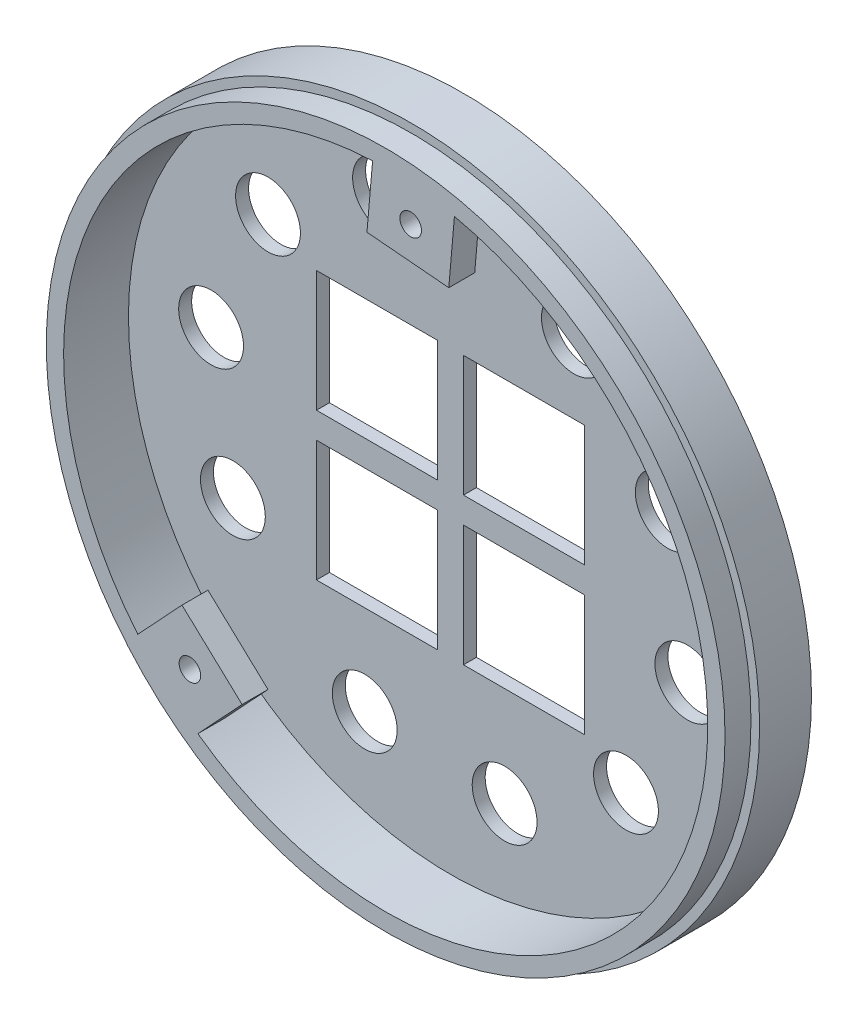
SolidWorks part; units mm, degrees
ref_plane "Front Plane" through (0, 0, 0) normal (1, 0, 0) x (0, 1, 0)
ref_plane "Top Plane" through (0, 0, 0) normal (0, 0, 1) x (0, 1, 0)
ref_plane "Right Plane" through (0, 0, 0) normal (0, 1, 0) x (-1, 0, 0)
sketch "Sketch2" plane through (0, 0, 0) normal (0, 0, 1) x (0, 1, 0)
  line L0 (-39.25, 0) -> (39.25, 0) construction
  line L1 (-23.781, 28.671) -> (30.26, -21.7231)
  line L2 (-30.26, 21.7231) -> (23.781, -28.671)
  line L3 (3.2395, 3.4739) -> (-3.2395, -3.4739) construction
  line L4 (-30.26, -21.7231) -> (23.781, 28.671)
  line L5 (-23.781, -28.671) -> (30.26, 21.7231)
  line L6 (-3.2395, 3.4739) -> (3.2395, -3.4739) construction
  line L7 (-36.3913, 7.952) -> (37.2193, 1.5119)
  line L8 (-37.2193, -1.5119) -> (36.3913, -7.952)
  line L9 (0.414, 4.7319) -> (-0.414, -4.7319) construction
  line L10 (-24.7749, 16.6081) -> (-18.2959, 23.556)
  line L11 (-24.7749, -16.6081) -> (-18.2959, -23.556)
  line L12 (29.7478, 2.1655) -> (28.9199, -7.2983)
  line L13 (-23.781, 28.671) -> (-24.7749, 16.6081) construction
  line L14 (-23.781, -28.671) -> (-24.7749, -16.6081) construction
  line L15 (29.7478, 2.1655) -> (36.3913, -7.952) construction
  circle A0 centre (0, 0) radius 39.25
  circle A1 centre (0, 0) radius 37.25
  circle A2 centre (-24.2779, 22.6396) radius 1.25
  circle A3 centre (-24.2779, -22.6396) radius 1.25
  circle A5 centre (33.0696, -2.8932) radius 1.25
  dimension "D1" = 78.5
  dimension "D12" = 2.5
  dimension "D3" = 9.5
  dimension "D4" = 43
  dimension "D5" = 9.5
  dimension "D6" = 43
  dimension "D7" = 9.5
  dimension "D8" = 5
  dimension "D9" = 7.5
  dimension "D10" = 7.5
  dimension "D11" = 7.5
  dimension "D2" = 2
extrude "Boss-Extrude1" add sketch "Sketch2" along normal blind 3 contours A0 A1 | L1 A1 L2 L10 | L8 A1 L7 L12 A5
sketch "Sketch3" plane through (0, 0, 0) normal (0, 0, 1) x (1, 0, 0)
  circle A0 centre (0, 0) radius 39.25 construction
  circle A1 centre (0, 0) radius 39.25 construction
  circle A2 centre (0, 0) radius 40.25
  circle A3 centre (2.8932, 33.0696) radius 1.25 construction
  circle A5 centre (-22.6396, -24.2779) radius 1.25 construction
  circle A6 centre (2.8932, 33.0696) radius 1.25
  circle A8 centre (-22.6396, -24.2779) radius 1.25
  arc A9 (-1.5119, 37.2193) -> (-28.671, -23.781) centre (0, 0) ccw construction
  arc A10 (-1.5119, 37.2193) -> (-28.671, -23.781) centre (0, 0) ccw construction
  circle A11 centre (0, 0) radius 37.25
  dimension "D1" = 80.5
extrude "Boss-Extrude2" add sketch "Sketch3" against normal blind 6
sketch "Sketch4" plane through (0, 0, -6) normal (0, 0, 1) x (1, 0, 0)
  circle A2 centre (0, 0) radius 40.25 construction
  circle A3 centre (0, 0) radius 40.25
extrude "Boss-Extrude3" add sketch "Sketch4" along normal blind 1.5
sketch "Sketch5" plane through (0, 0, -6) normal (0, 0, -1) x (-1, 0, 0)
  line L1 (-8.5, -8.5) -> (8.5, -8.5) construction
  line L2 (-8.5, -8.5) -> (-8.5, 8.5) construction
  line L3 (-8.5, 8.5) -> (8.5, 8.5) construction
  line L4 (8.5, -8.5) -> (8.5, 8.5) construction
  line L5 (-8.5, -8.5) -> (8.5, 8.5) construction
  line L6 (-8.5, 8.5) -> (8.5, -8.5) construction
  line L7 (-15.5, -1.5) -> (-1.5, -1.5)
  line L8 (-15.5, -1.5) -> (-15.5, -15.5)
  line L9 (-15.5, -15.5) -> (-1.5, -15.5)
  line L10 (-1.5, -1.5) -> (-1.5, -15.5)
  line L11 (-15.5, -1.5) -> (-1.5, -15.5) construction
  line L12 (-15.5, -15.5) -> (-1.5, -1.5) construction
  line L13 (-15.5, 1.5) -> (-1.5, 1.5)
  line L14 (-15.5, 1.5) -> (-15.5, 15.5)
  line L15 (-15.5, 15.5) -> (-1.5, 15.5)
  line L16 (-1.5, 1.5) -> (-1.5, 15.5)
  line L17 (-15.5, 1.5) -> (-1.5, 15.5) construction
  line L18 (-15.5, 15.5) -> (-1.5, 1.5) construction
  line L19 (1.5, 1.5) -> (15.5, 1.5)
  line L20 (1.5, 1.5) -> (1.5, 15.5)
  line L21 (1.5, 15.5) -> (15.5, 15.5)
  line L22 (15.5, 1.5) -> (15.5, 15.5)
  line L23 (1.5, 1.5) -> (15.5, 15.5) construction
  line L24 (1.5, 15.5) -> (15.5, 1.5) construction
  line L25 (1.5, -1.5) -> (15.5, -1.5)
  line L26 (1.5, -1.5) -> (1.5, -15.5)
  line L27 (1.5, -15.5) -> (15.5, -15.5)
  line L28 (15.5, -1.5) -> (15.5, -15.5)
  line L29 (1.5, -1.5) -> (15.5, -15.5) construction
  line L30 (1.5, -15.5) -> (15.5, -1.5) construction
  point P24 (0, 0)
  dimension "D2" = 17
  dimension "D3" = 14
  dimension "D4" = 14
extrude "Cut-Extrude1" cut sketch "Sketch5" against normal up to surface (1.5 mm away) contours L10 L7 L8 L9 | L13 L16 L15 L14 | L19 L22 L21 L20 | L28 L25 L26 L27 up to face at (37.25, 0, -4.5)
sketch "Sketch7" plane through (0, 0, -6) normal (0, 0, -1) x (-1, 0, 0)
  line L0 (-5.6407, -25.115) -> (-8.0671, -26.17) construction
  line L1 (-18.7205, -17.667) -> (-21.322, -17.1848) construction
  line L2 (-25.3992, -4.1783) -> (-27.2864, -2.3238) construction
  line L3 (-23.3934, 10.7391) -> (-23.9209, 13.3319) construction
  line L4 (-13.3887, 21.9846) -> (-12.3762, 24.429) construction
  line L5 (6.994, 24.9791) -> (9.4016, 26.0763) construction
  line L6 (19.5696, 17.0265) -> (22.1841, 16.6202) construction
  line L7 (25.7064, 3.4717) -> (27.6674, 1.6956) construction
  line L8 (23.3851, -11.2253) -> (24.0476, -13.7869) construction
  line L9 (9.3677, -23.9755) -> (7.9461, -26.207) construction
  line L10 (-5.6407, -25.115) -> (-8.0671, -26.17) construction
  line L11 (-18.7205, -17.667) -> (-21.322, -17.1848) construction
  line L12 (-25.3992, -4.1783) -> (-27.2864, -2.3238) construction
  line L13 (-23.3934, 10.7391) -> (-23.9209, 13.3319) construction
  line L14 (-13.3887, 21.9846) -> (-12.3762, 24.429) construction
  line L15 (6.994, 24.9791) -> (9.4016, 26.0763) construction
  line L16 (19.5696, 17.0265) -> (22.1841, 16.6202) construction
  line L17 (25.7064, 3.4717) -> (27.6674, 1.6956) construction
  line L18 (23.3851, -11.2253) -> (24.0476, -13.7869) construction
  line L19 (9.3677, -23.9755) -> (7.9461, -26.207) construction
  arc A0 (-8.0671, -26.17) -> (-5.6407, -25.115) centre (-6.2558, -27.018) ccw construction
  arc A1 (-21.322, -17.1848) -> (-18.7205, -17.667) centre (-20.2946, -18.9008) ccw construction
  arc A2 (-27.2864, -2.3238) -> (-25.3992, -4.1783) centre (-27.3941, -4.3209) ccw construction
  arc A3 (-23.9209, 13.3319) -> (-23.3934, 10.7391) centre (-25.127, 11.7365) ccw construction
  arc A4 (-12.3762, 24.429) -> (-13.3887, 21.9846) centre (-14.2682, 23.7808) ccw construction
  arc A5 (9.4016, 26.0763) -> (6.994, 24.9791) centre (7.5758, 26.8926) ccw construction
  arc A6 (22.1841, 16.6202) -> (19.5696, 17.0265) centre (21.1072, 18.3055) ccw construction
  arc A7 (27.6674, 1.6956) -> (25.7064, 3.4717) centre (27.6938, 3.6954) ccw construction
  arc A8 (24.0476, -13.7869) -> (23.3851, -11.2253) centre (25.1685, -12.1305) ccw construction
  arc A9 (7.9461, -26.207) -> (9.3677, -23.9755) centre (9.922, -25.8972) ccw construction
  arc A10 (-8.0671, -26.17) -> (-5.6407, -25.115) centre (-6.2558, -27.018) ccw construction
  arc A11 (-21.322, -17.1848) -> (-18.7205, -17.667) centre (-20.2946, -18.9008) ccw construction
  arc A12 (-27.2864, -2.3238) -> (-25.3992, -4.1783) centre (-27.3941, -4.3209) ccw construction
  arc A13 (-23.9209, 13.3319) -> (-23.3934, 10.7391) centre (-25.127, 11.7365) ccw construction
  arc A14 (-12.3762, 24.429) -> (-13.3887, 21.9846) centre (-14.2682, 23.7808) ccw construction
  arc A15 (9.4016, 26.0763) -> (6.994, 24.9791) centre (7.5758, 26.8926) ccw construction
  arc A16 (22.1841, 16.6202) -> (19.5696, 17.0265) centre (21.1072, 18.3055) ccw construction
  arc A17 (27.6674, 1.6956) -> (25.7064, 3.4717) centre (27.6938, 3.6954) ccw construction
  arc A18 (24.0476, -13.7869) -> (23.3851, -11.2253) centre (25.1685, -12.1305) ccw construction
  arc A19 (7.9461, -26.207) -> (9.3677, -23.9755) centre (9.922, -25.8972) ccw construction
  circle A20 centre (-25.127, 11.7365) radius 3.75
  circle A21 centre (-27.3941, -4.3209) radius 3.75
  circle A22 centre (-20.2946, -18.9008) radius 3.75
  circle A23 centre (-6.2558, -27.018) radius 3.75
  circle A24 centre (9.922, -25.8972) radius 3.75
  circle A25 centre (25.1685, -12.1305) radius 3.75
  circle A26 centre (27.6938, 3.6954) radius 3.75
  circle A27 centre (21.1072, 18.3055) radius 3.75
  circle A28 centre (7.5758, 26.8926) radius 3.75
  circle A29 centre (-14.2682, 23.7808) radius 3.75
  dimension "D1" = 7.5
extrude "Cut-Extrude2" cut sketch "Sketch7" against normal up to surface (1.5 mm away) up to face at (-8.5, -8.5, -4.5)
